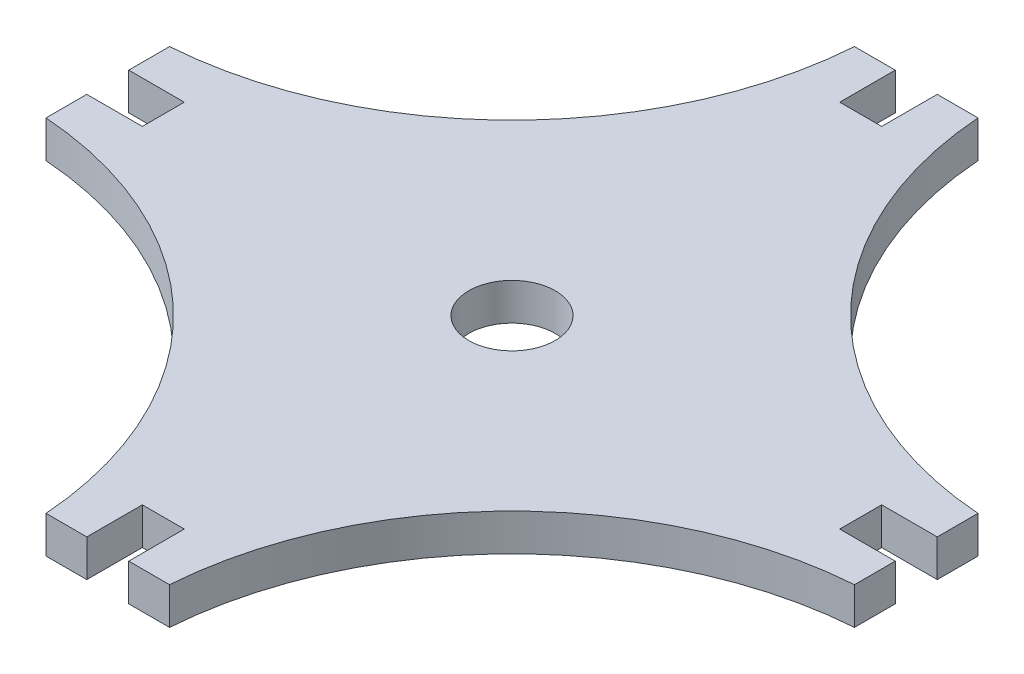
SolidWorks part; units mm, degrees
material "Thornel Mat VMA"
ref_plane "Front Plane" through (0, 0, 0) normal (0, 0, 1) x (1, 0, 0)
ref_plane "Top Plane" through (0, 0, 0) normal (0, 1, 0) x (1, 0, 0)
ref_plane "Right Plane" through (0, 0, 0) normal (1, 0, 0) x (0, 0, -1)
sketch "Sketch1" plane through (0, 0, 0) normal (0, 1, 0) x (1, 0, 0)
  line L0 (0, 0) -> (0, 28.25) construction
  line L1 (-1.7, 28.25) -> (1.7, 28.25)
  line L2 (1.7, 28.25) -> (1.7, 32.75)
  line L3 (-1.7, 28.25) -> (-1.7, 32.75)
  line L4 (-1.7, 32.75) -> (-5.0039, 32.75)
  line L5 (1.7, 32.75) -> (5.0039, 32.75)
  line L6 (0, 0) -> (-28.25, 0) construction
  line L7 (-34.925, -34.925) -> (34.925, -34.925) construction
  line L8 (-34.925, -34.925) -> (-34.925, 34.925) construction
  line L9 (-34.925, 34.925) -> (34.925, 34.925) construction
  line L10 (34.925, -34.925) -> (34.925, 34.925) construction
  line L11 (-34.925, -34.925) -> (34.925, 34.925) construction
  line L12 (-34.925, 34.925) -> (34.925, -34.925) construction
  line L13 (0, 0) -> (0, -28.25) construction
  line L14 (0, 0) -> (28.25, 0) construction
  line L15 (-28.25, -1.7) -> (-28.25, 1.7)
  line L16 (-28.25, 1.7) -> (-32.75, 1.7)
  line L17 (28.25, -1.7) -> (28.25, 1.7)
  line L18 (28.25, 1.7) -> (32.75, 1.7)
  line L19 (-1.7, -28.25) -> (1.7, -28.25)
  line L20 (1.7, -28.25) -> (1.7, -32.75)
  line L21 (-28.25, -1.7) -> (-32.75, -1.7)
  line L22 (-32.75, 1.7) -> (-32.75, 5.0039)
  line L23 (-1.7, -28.25) -> (-1.7, -32.75)
  line L24 (28.25, -1.7) -> (32.75, -1.7)
  line L25 (-32.75, -1.7) -> (-32.75, -5.0039)
  line L26 (-1.7, -32.75) -> (-5.0039, -32.75)
  line L27 (1.7, -32.75) -> (5.0039, -32.75)
  line L28 (32.75, -1.7) -> (32.75, -5.0039)
  line L29 (32.75, 1.7) -> (32.75, 5.0039)
  circle A0 centre (0, 0) radius 3.5
  circle A1 centre (-34.925, 34.925) radius 30 construction
  circle A2 centre (34.925, 34.925) radius 30 construction
  circle A3 centre (34.925, -34.925) radius 30 construction
  circle A4 centre (-34.925, -34.925) radius 30 construction
  arc A5 (-5.0039, 32.75) -> (-32.75, 5.0039) centre (-34.925, 34.925) cw
  arc A6 (-32.75, -5.0039) -> (-5.0039, -32.75) centre (-34.925, -34.925) cw
  arc A7 (5.0039, -32.75) -> (32.75, -5.0039) centre (34.925, -34.925) cw
  arc A8 (5.0039, 32.75) -> (32.75, 5.0039) centre (34.925, 34.925) ccw
  point P7 (0, 28.25)
  point P25 (-28.25, 0)
  point P29 (28.25, 0)
  point P32 (0, -28.25)
  dimension "D2" = 7
  dimension "D7" = 60
  dimension "D1" = 28.25
  dimension "D3" = 4.5
  dimension "D4" = 3.4
  dimension "D5" = 69.85
  dimension "D6" = 69.85
extrude "Boss-Extrude1" add sketch "Sketch1" along normal mid plane 3
